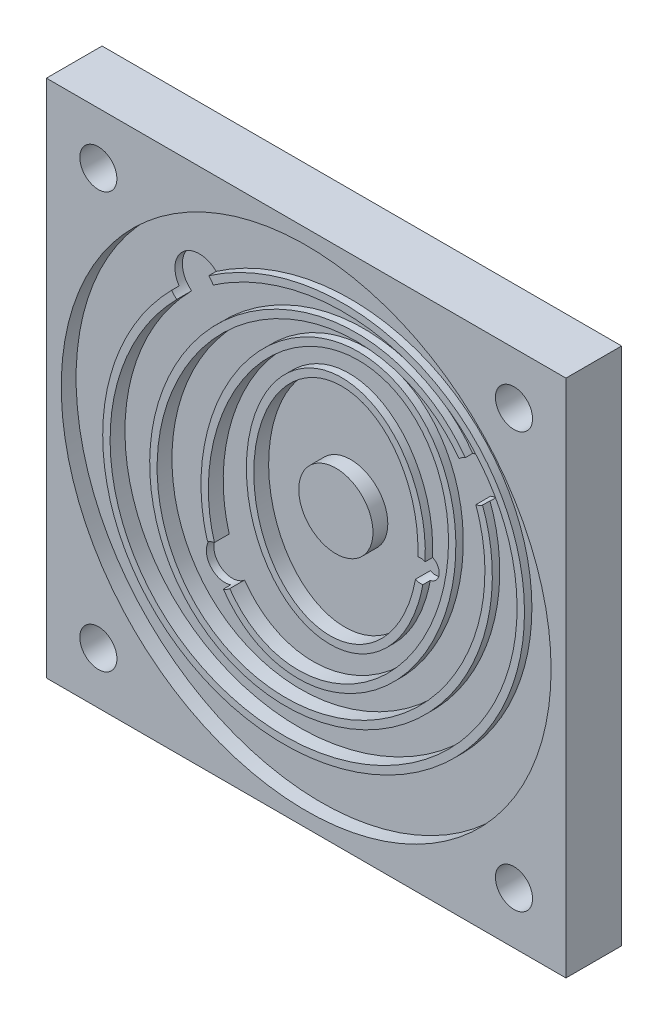
SolidWorks part; units mm, degrees
ref_plane "Front Plane" through (0, 0, 0) normal (0, 0, 1) x (1, 0, 0)
ref_plane "Top Plane" through (0, 0, 0) normal (0, 1, 0) x (1, 0, 0)
ref_plane "Right Plane" through (0, 0, 0) normal (1, 0, 0) x (0, 0, -1)
sketch "Sketch1" plane through (0, 0, 0) normal (0, 0, 1) x (1, 0, 0)
  line L1 (-44.45, 44.45) -> (44.45, 44.45)
  line L2 (-44.45, 44.45) -> (-44.45, -44.45)
  line L3 (-44.45, -44.45) -> (44.45, -44.45)
  line L4 (44.45, 44.45) -> (44.45, -44.45)
  line L5 (-44.45, 44.45) -> (44.45, -44.45) construction
  line L6 (-44.45, -44.45) -> (44.45, 44.45) construction
  point P0 (0, 0)
  dimension "D1" = 88.9
  dimension "D2" = 88.9
extrude "Boss-Extrude1" add sketch "Sketch1" along normal blind 8.89 and the other way blind 0.635
sketch "Sketch5" plane through (0, 0, -0.635) normal (0, 0, -1) x (-1, 0, 0)
  ellipse E0 centre (0, 0) end of major axis (28.2011, -23.6885) minor radius 31.75
  ellipse E1 centre (0, 0) end of major axis (-29.1736, 24.5054) minor radius 33.02
ref_plane "Plane5" through (0, 0, 0.635) normal (0, 0, -1) x (-1, 0, 0)
extrude "Boss-Extrude4" add sketch "Sketch5" against normal up to surface (9.525 mm away) up to face at (0, 0, 8.89)
sketch "Sketch10" plane through (0, 0, -0.635) normal (0, 0, -1) x (-1, 0, 0)
  ellipse E0 centre (0, 0) end of major axis (-20.6449, 25.7703) minor radius 26.67
  ellipse E1 centre (0, 0) end of major axis (-19.8164, 24.8067) minor radius 25.4
sketch "Sketch12" plane through (0, 0, -0.635) normal (0, 0, -1) x (-1, 0, 0)
  ellipse E0 centre (0, 0) end of major axis (-11.5282, 25.4508) minor radius 20.32
  ellipse E1 centre (0, 0) end of major axis (11.0042, -24.294) minor radius 19.05
sketch "Sketch13" plane through (0, 0, -0.635) normal (0, 0, -1) x (-1, 0, 0)
  ellipse E0 centre (0, 0) end of major axis (2.2617, -20.1937) minor radius 15.24
  ellipse E1 centre (0, 0) end of major axis (-2.1203, 18.9316) minor radius 13.97
sketch "Sketch18" plane through (0, 0, 8.89) normal (0, 0, 1) x (1, 0, 0)
  line L0 (0, 44.45) -> (0, -44.45) construction
  line L1 (44.45, 44.45) -> (-44.45, 44.45) construction
  line L2 (-44.45, -44.45) -> (44.45, -44.45) construction
  line L3 (-44.45, 0) -> (44.45, 0) construction
  line L4 (-44.45, 44.45) -> (-44.45, -44.45) construction
  line L5 (44.45, -44.45) -> (44.45, 44.45) construction
  circle A0 centre (-35.56, -35.56) radius 3.175
  circle A1 centre (35.56, -35.56) radius 3.175
  circle A2 centre (35.56, 35.56) radius 3.175
  circle A3 centre (-35.56, 35.56) radius 3.175
  dimension "D1" = 35.56
  dimension "D2" = 35.56
extrude "Cut-Extrude6" cut sketch "Sketch18" against normal blind 5.08
sketch "Sketch39" plane through (0, 0, 8.89) normal (0, 0, 1) x (1, 0, 0)
  circle A0 centre (-20.8256, 24.8009) radius 4.1673
  circle A1 centre (25.7931, 18.5296) radius 3.175
  circle A2 centre (14.5143, -1.6256) radius 1.8987
  circle A3 centre (-18.9881, -16.9362) radius 3.175
  circle A4 centre (0, 0) radius 41.91
  ellipse E0 centre (0, 0) end of major axis (-2.1203, -18.9316) minor radius 13.97
  ellipse E3 centre (0, 0) end of major axis (-2.2617, -20.1937) minor radius 15.24
  ellipse E5 centre (0, 0) end of major axis (11.0042, 24.294) minor radius 19.05
  ellipse E8 centre (0, 0) end of major axis (11.5282, 25.4508) minor radius 20.32
  ellipse E11 centre (0, 0) end of major axis (19.8164, 24.8067) minor radius 25.4
  ellipse E14 centre (0, 0) end of major axis (-20.6449, -25.7703) minor radius 26.67
  ellipse E17 centre (0, 0) end of major axis (28.2011, 23.6885) minor radius 31.75
  ellipse E20 centre (0, 0) end of major axis (29.1736, 24.5054) minor radius 33.02
  point P146 (-21.238, 25.2838)
  point P161 (-20.4211, 24.3113)
  point P162 (11.5282, 25.4508)
  point P163 (11.0042, 24.294)
  point P164 (19.8164, 24.8067)
  point P165 (28.2011, 23.6885)
  point P166 (-2.1203, -18.9316)
  point P167 (25.7931, 18.5296)
  point P168 (14.5143, -1.6256)
  point P169 (-2.2617, -20.1937)
  point P170 (-20.6449, -25.7703)
  point P171 (-18.9881, -16.9362)
  point P172 (21.238, -25.2838)
  point P173 (-21.238, 25.4508)
  point P174 (-20.8256, 24.8009)
sketch "Sketch40" plane through (0, 0, 8.89) normal (0, 0, 1) x (1, 0, 0)
  circle A0 centre (0, 0) radius 41.91
  circle A1 centre (-20.8256, 24.8009) radius 4.1673
sketch "Sketch41" plane through (0, 0, 8.89) normal (0, 0, 1) x (1, 0, 0)
  circle A0 centre (0, 0) radius 41.91
  arc A1 (-17.9345, 27.8021) -> (-24.2814, 22.4721) centre (-20.8256, 24.8009) ccw
  ellipse E0 centre (0, 0) end of major axis (-29.1736, -24.5054) minor radius 33.02 (-24.2814, 22.4721) -> (-17.9345, 27.8021) ccw
extrude "Cut-Extrude7" cut sketch "Sketch41" against normal blind 2.54
sketch "Sketch42" plane through (0, 0, 8.89) normal (0, 0, 1) x (1, 0, 0)
  arc A0 (-23.4185, 21.5385) -> (-17.1642, 26.7908) centre (-20.8256, 24.8009) ccw
  arc A1 (27.6439, 15.9499) -> (24.6917, 21.5074) centre (25.7931, 18.5296) ccw
  ellipse E0 centre (0, 0) end of major axis (-28.2011, -23.6885) minor radius 31.75 (-23.4185, 21.5385) -> (-17.1642, 26.7908) ccw
  ellipse E1 centre (0, 0) end of major axis (20.6449, 25.7703) minor radius 26.67 (24.6917, 21.5074) -> (27.6439, 15.9499) ccw
extrude "Cut-Extrude8" cut sketch "Sketch42" against normal blind 3.81
sketch "Sketch43" plane through (0, 0, 8.89) normal (0, 0, 1) x (1, 0, 0)
  arc A0 (23.6085, 20.8336) -> (26.48, 15.4298) centre (25.7931, 18.5296) ccw
  arc A1 (-20.6852, -14.2528) -> (-17.9859, -19.9489) centre (-18.9881, -16.9362) ccw
  ellipse E0 centre (0, 0) end of major axis (-19.8164, -24.8067) minor radius 25.4 (23.6085, 20.8336) -> (26.48, 15.4298) ccw
  ellipse E1 centre (0, 0) end of major axis (-11.5282, -25.4508) minor radius 20.32 (-17.9859, -19.9489) -> (-20.6852, -14.2528) ccw
extrude "Cut-Extrude9" cut sketch "Sketch43" against normal blind 5.08
sketch "Sketch44" plane through (0, 0, 8.89) normal (0, 0, 1) x (1, 0, 0)
  arc A0 (-16.8902, -19.3194) -> (-19.5114, -13.8046) centre (-18.9881, -16.9362) ccw
  arc A1 (14.8837, -3.4879) -> (15.2865, 0.1089) centre (14.5143, -1.6256) ccw
  ellipse E0 centre (0, 0) end of major axis (-11.0042, -24.294) minor radius 19.05 (-16.8902, -19.3194) -> (-19.5114, -13.8046) ccw
  ellipse E1 centre (0, 0) end of major axis (-2.2617, -20.1937) minor radius 15.24 (15.2865, 0.1089) -> (14.8837, -3.4879) ccw
extrude "Cut-Extrude10" cut sketch "Sketch44" against normal blind 6.35
sketch "Sketch45" plane through (0, 0, 8.89) normal (0, 0, 1) x (1, 0, 0)
  arc A0 (14.02, 0.2076) -> (13.6267, -3.304) centre (14.5143, -1.6256) ccw
  circle A1 centre (0, 0) radius 6.35
  ellipse E0 centre (0, 0) end of major axis (-2.1203, -18.9316) minor radius 13.97 (14.02, 0.2076) -> (13.6267, -3.304) ccw
extrude "Cut-Extrude11" cut sketch "Sketch45" against normal blind 7.62
sketch "Sketch46" plane through (0, 0, 8.89) normal (0, 0, 1) x (1, 0, 0)
  circle A0 centre (-20.8256, 24.8009) radius 4.1673
extrude "Cut-Extrude12" cut sketch "Sketch46" against normal up to surface (3.81 mm away) up to face at (1.1277, 0.583, 5.08)
sketch "Sketch47" plane through (0, 0, 8.89) normal (0, 0, 1) x (1, 0, 0)
  circle A0 centre (25.7931, 18.5296) radius 3.175
extrude "Cut-Extrude13" cut sketch "Sketch47" against normal up to surface (5.08 mm away) up to face at (-1.1661, -0.5137, 3.81)
sketch "Sketch49" plane through (0, 0, 8.89) normal (0, 0, 1) x (1, 0, 0)
  circle A0 centre (-18.9881, -16.9362) radius 3.175
extrude "Cut-Extrude14" cut sketch "Sketch49" against normal up to surface (6.35 mm away) up to face at (0.6279, -0.0703, 2.54)
sketch "Sketch50" plane through (0, 0, 8.89) normal (0, 0, 1) x (1, 0, 0)
  circle A0 centre (14.5143, -1.6256) radius 1.8987
extrude "Cut-Extrude15" cut sketch "Sketch50" against normal up to surface (7.62 mm away) up to face at (6.35, 0, 1.27)
sketch "Sketch51" plane through (0, 0, 8.89) normal (0, 0, 1) x (1, 0, 0)
  ellipse E0 centre (0, 0) end of major axis (-29.1736, -24.5054) minor radius 33.02
  ellipse E1 centre (0, 0) end of major axis (-29.1736, -24.5054) minor radius 33.02 (-24.2814, 22.4721) -> (-17.9345, 27.8021) ccw construction
  ellipse E2 centre (0, 0) end of major axis (-29.1736, -24.5054) minor radius 33.02 (-24.2814, 22.4721) -> (-17.9345, 27.8021) ccw construction
extrude "Cut-Extrude16" cut sketch "Sketch51" against normal offset from surface (1.27 mm away) 1.27 up to face at (-1.1358, 1.3525, 6.35)
sketch "Sketch52" plane through (0, 0, 8.89) normal (0, 0, 1) x (1, 0, 0)
  ellipse E0 centre (0, 0) end of major axis (-20.6449, -25.7703) minor radius 26.67
  ellipse E1 centre (0, 0) end of major axis (20.6449, 25.7703) minor radius 26.67 (24.6917, 21.5074) -> (27.6439, 15.9499) ccw construction
  ellipse E2 centre (0, 0) end of major axis (20.6449, 25.7703) minor radius 26.67 (24.6917, 21.5074) -> (27.6439, 15.9499) ccw construction
extrude "Cut-Extrude19" cut sketch "Sketch52" against normal offset from surface (2.54 mm away) 1.27 up to face at (1.1277, 0.583, 5.08)
sketch "Sketch53" plane through (0, 0, 8.89) normal (0, 0, 1) x (1, 0, 0)
  ellipse E0 centre (0, 0) end of major axis (-11.5282, -25.4508) minor radius 20.32
  ellipse E1 centre (0, 0) end of major axis (-11.5282, -25.4508) minor radius 20.32 (-17.9859, -19.9489) -> (-20.6852, -14.2528) ccw construction
  ellipse E2 centre (0, 0) end of major axis (-11.5282, -25.4508) minor radius 20.32 (-17.9859, -19.9489) -> (-20.6852, -14.2528) ccw construction
extrude "Cut-Extrude20" cut sketch "Sketch53" against normal offset from surface (3.81 mm away) 1.27 up to face at (-1.1661, -0.5137, 3.81)
sketch "Sketch54" plane through (0, 0, 8.89) normal (0, 0, 1) x (1, 0, 0)
  ellipse E0 centre (0, 0) end of major axis (-2.2617, -20.1937) minor radius 15.24
  ellipse E1 centre (0, 0) end of major axis (-2.2617, -20.1937) minor radius 15.24 (15.2865, 0.1089) -> (14.8837, -3.4879) ccw construction
  ellipse E2 centre (0, 0) end of major axis (-2.2617, -20.1937) minor radius 15.24 (15.2865, 0.1089) -> (14.8837, -3.4879) ccw construction
extrude "Cut-Extrude21" cut sketch "Sketch54" against normal offset from surface (5.08 mm away) 1.27 up to face at (0.6279, -0.0703, 2.54)
